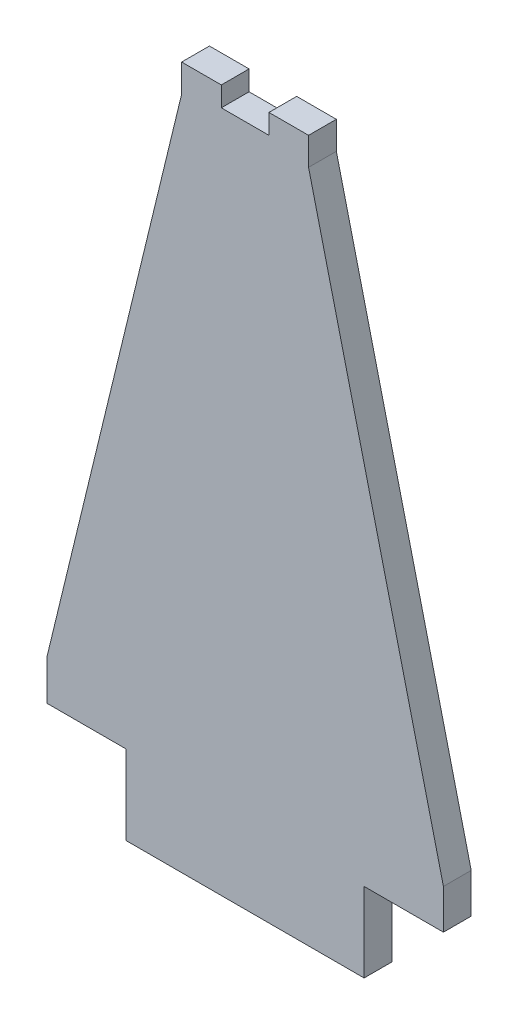
SolidWorks part; units mm, degrees
material "PBT General Purpose"
ref_plane "Front Plane" through (0, 0, 0) normal (0, 0, 1) x (1, 0, 0)
ref_plane "Top Plane" through (0, 0, 0) normal (0, 1, 0) x (1, 0, 0)
ref_plane "Right Plane" through (0, 0, 0) normal (1, 0, 0) x (0, 0, -1)
sketch "frame_outline" plane through (0, 0, 0) normal (0, 0, 1) x (1, 0, 0)
  line L110 (0, 0) -> (3, 0)
  line L117 (3, 0) -> (3, 1)
  line L118 (3, 1) -> (4, 1)
  line L119 (4, 1) -> (4, 1.5)
  line L120 (4, 1.5) -> (2.3, 8.5)
  line L121 (2.3, 8.5) -> (2.3, 8.85)
  line L122 (2.3, 8.85) -> (1.8, 8.85)
  line L123 (1.8, 8.85) -> (1.8, 8.6)
  line L124 (1.8, 8.6) -> (1.2, 8.6)
  line L125 (1.2, 8.6) -> (1.2, 8.85)
  line L126 (1.2, 8.85) -> (0.7, 8.85)
  line L127 (0.7, 8.85) -> (0.7, 8.5)
  line L128 (0.7, 8.5) -> (-1, 1.5)
  line L129 (-1, 1.5) -> (-1, 1)
  line L130 (-1, 1) -> (0, 1)
  line L131 (0, 1) -> (0, 0)
  line L132 (1.5, 8.6) -> (1.5, 0) construction
  dimension "D1" = 5
  dimension "D2" = 3
  dimension "D3" = 1
  dimension "D4" = 0.5
  dimension "D5" = 7.5
  dimension "D6" = 0.6
  dimension "D7" = 0.25
  dimension "D8" = 0.5
  dimension "D9" = 0.1
extrude "Boss-Extrude1" add sketch "frame_outline" along normal mid plane 0.35
equation "\"t\"= 0.25'thickness of the sheets"
equation "\"t_cf\" = 0.115'thickness of single carbon fiber layer"
equation "\"t_kapton\" = 0.025'thickness of single Kapton flex layer"
equation "\"t_fr4\" = 0.1'thickness of FR4 with copper layer"
equation "\"joint_flex\"= 0.1'Width of flextures gap"
equation "\"joint_flex_eff\"= 0.02'Width of flecture after castelation"
equation "\"joint_fold\"= 0.2'Width of folding joints for 90deg fold"
equation "\"gap_tolerance\"= 0.002'Width to have interfecence fit between carbon fiber inserts"
equation "\"assemble_angle\"= 90'Angle of assembly parts"
equation "\"D1@Boss-Extrude1\"=0.35"
equation "\"link_lift\"= 0.5'Actuation linkage amplification for the lift motion"
equation "\"link_swing\"= 0.45'Actuation linkage amplification for the swing motion"
